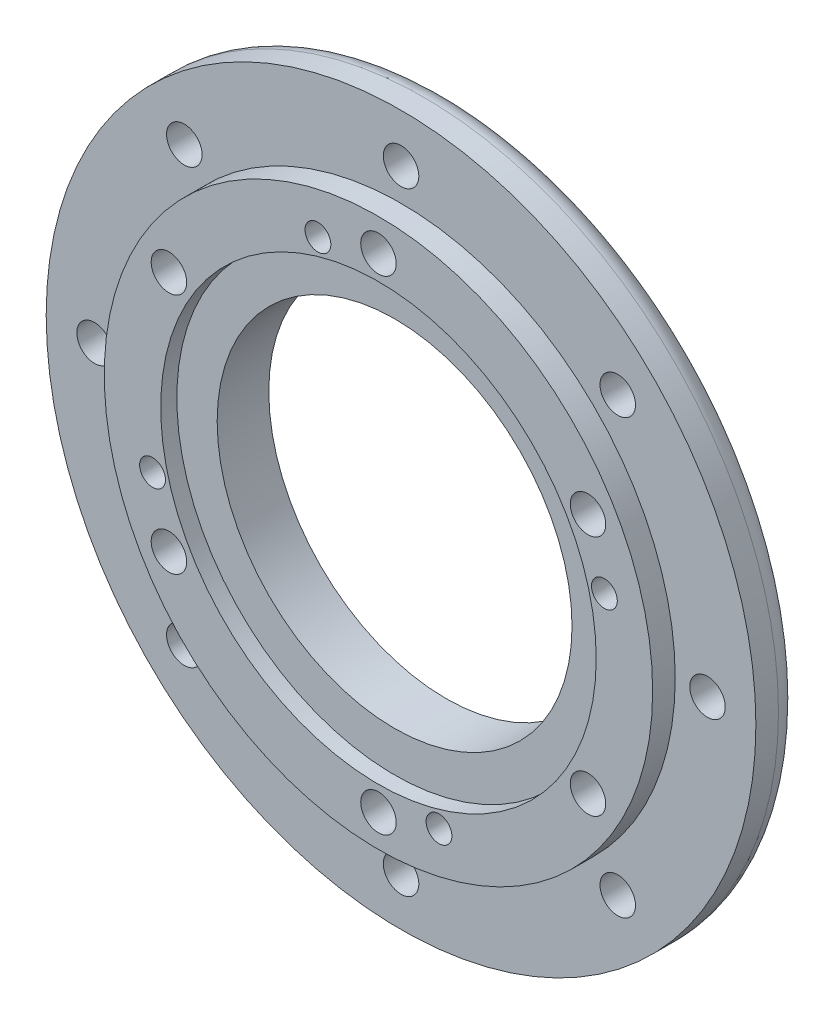
SolidWorks part; units mm, degrees
ref_plane "前视基准面" through (0, 0, 0) normal (0, 0, 1) x (1, 0, 0)
ref_plane "上视基准面" through (0, 0, 0) normal (0, 1, 0) x (1, 0, 0)
ref_plane "右视基准面" through (0, 0, 0) normal (1, 0, 0) x (0, 0, -1)
sketch "草图1" plane through (0, 0, 0) normal (0, 0, 1) x (1, 0, 0)
  circle A0 centre (0, 0) radius 110
extrude "拉伸1" add sketch "草图1" along normal blind 14
sketch "草图2" plane through (0, 0, 14) normal (0, 0, 1) x (1, 0, 0)
  circle A0 centre (0, 0) radius 85
  dimension "D1" = 170
extrude "拉伸2" add sketch "草图2" along normal blind 7
sketch "草图3" plane through (0, 0, 0) normal (0, 0, -1) x (-1, 0, 0)
  circle A0 centre (0, 0) radius 55
extrude "切除-拉伸1" cut sketch "草图3" against normal through all
fillet "圆角1" radius 7 1 edges at (110, 0, 0)
sketch "草图5" plane through (0, 0, 0) normal (0, 0, -1) x (-1, 0, 0)
  circle A1 centre (0, 95) radius 5.5
  circle A2 centre (67.1751, 67.1751) radius 5.5
  circle A3 centre (95, 0) radius 5.5
  circle A4 centre (67.1751, -67.1751) radius 5.5
  circle A5 centre (0, -95) radius 5.5
  circle A6 centre (-67.1751, -67.1751) radius 5.5
  circle A7 centre (-95, 0) radius 5.5
  circle A8 centre (-67.1751, 67.1751) radius 5.5
  dimension "D1" = 11
extrude "切除-拉伸2" cut sketch "草图5" against normal through all
sketch "草图6" plane through (0, 0, 0) normal (0, 0, -1) x (-1, 0, 0)
  circle A1 centre (0, 75) radius 5.5
  circle A2 centre (64.9519, 37.5) radius 5.5
  circle A3 centre (64.9519, -37.5) radius 5.5
  circle A4 centre (0, -75) radius 5.5
  circle A5 centre (-64.9519, -37.5) radius 5.5
  circle A6 centre (-64.9519, 37.5) radius 5.5
extrude "切除-拉伸3" cut sketch "草图6" against normal through all
sketch "草图7" plane through (0, 0, 21) normal (0, 0, 1) x (1, 0, 0)
  circle A0 centre (0, 0) radius 67.5
extrude "切除-拉伸4" cut sketch "草图7" against normal blind 5
sketch "草图8" plane through (0, 0, 0) normal (0, 0, -1) x (-1, 0, 0)
  circle A0 centre (0, 75) radius 9
  circle A1 centre (64.9519, 37.5) radius 9
  circle A2 centre (64.9519, -37.5) radius 9
  circle A3 centre (0, -75) radius 9
  circle A4 centre (-64.9519, -37.5) radius 9
  circle A5 centre (-64.9519, 37.5) radius 9
extrude "切除-拉伸5" cut sketch "草图8" against normal blind 11
sketch "草图10" plane through (0, 0, 0) normal (0, 0, -1) x (-1, 0, 0)
  circle A1 centre (18.7644, 70.0296) radius 4
  circle A2 centre (70.0296, -18.7644) radius 4
  circle A3 centre (-18.7644, -70.0296) radius 4
  circle A4 centre (-70.0296, 18.7644) radius 4
extrude "切除-拉伸6" cut sketch "草图10" against normal through all
